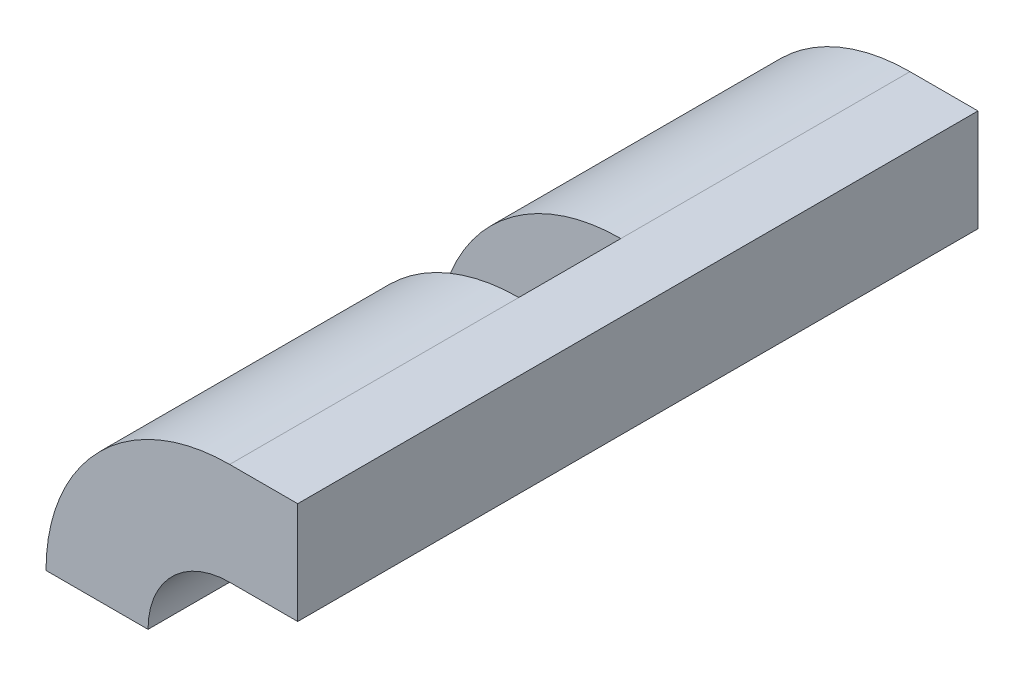
SolidWorks part; units mm, degrees
ref_plane "前视基准面" through (0, 0, 0) normal (0, 0, 1) x (1, 0, 0)
ref_plane "上视基准面" through (0, 0, 0) normal (0, 1, 0) x (1, 0, 0)
ref_plane "右视基准面" through (0, 0, 0) normal (1, 0, 0) x (0, 0, -1)
sketch "草图1" plane through (0, 0, 0) normal (0, 0, 1) x (1, 0, 0)
  line L0 (-74, -24) -> (-44, -24)
  line L1 (0, 0) -> (-20, 0)
  line L2 (0, 0) -> (0, 30)
  line L3 (0, 30) -> (-20, 30)
  arc A0 (-20, 30) -> (-74, -24) centre (-20, -24) ccw
  arc A1 (-20, 0) -> (-44, -24) centre (-20, -24) ccw
  dimension "D3" = 24
  dimension "D1" = 20
  dimension "D2" = 30
extrude "凸台-拉伸1" add sketch "草图1" along normal blind 200
ref_plane "基准面1" through (-74, 0, 0) normal (-1, 0, 0) x (0, 0, 1)
sketch "草图2" plane through (-74, 0, 0) normal (-1, 0, 0) x (0, 0, 1)
  line L0 (85, -24) -> (85, 34.0239)
  line L3 (85, 34.0239) -> (115, 34.0239)
  line L4 (115, 34.0239) -> (115, -24)
  line L5 (115, -24) -> (85, -24)
  line L8 (200, -24) -> (200, 30) construction
  line L9 (0, 30) -> (0, -24) construction
  dimension "D1" = 85
  dimension "D2" = 85
extrude "切除-拉伸1" cut sketch "草图2" against normal blind 54
